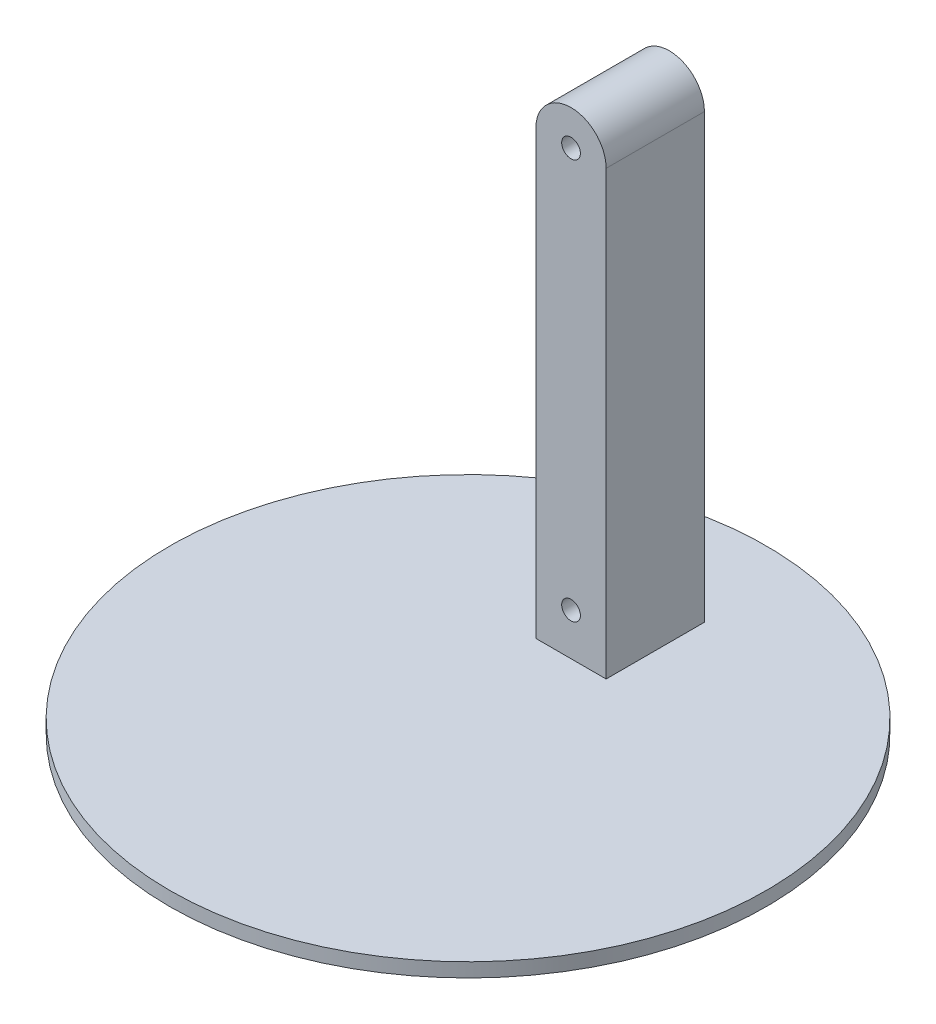
SolidWorks part; units mm, degrees
ref_plane "Front Plane" through (0, 0, 0) normal (0, 0, 1) x (1, 0, 0)
ref_plane "Top Plane" through (0, 0, 0) normal (0, 1, 0) x (1, 0, 0)
ref_plane "Right Plane" through (0, 0, 0) normal (1, 0, 0) x (0, 0, -1)
sketch "Sketch1" plane through (0, 0, 0) normal (0, 1, 0) x (1, 0, 0)
  circle A0 centre (0, 0) radius 127.5
  dimension "D1" = 255
extrude "Boss-Extrude1" add sketch "Sketch1" along normal blind 6 from offset 195 offset against normal yes
sketch "Sketch2" plane through (0, 0, 0) normal (0, 0, 1) x (1, 0, 0)
  line L0 (-15, 0) -> (-15, -189)
  line L1 (127.5, -189) -> (-127.5, -189) construction
  line L2 (-15, -189) -> (15, -189)
  line L3 (15, -189) -> (15, 0)
  circle A0 centre (0, 0) radius 4
  circle A1 centre (0, -171) radius 4
  arc A2 (15, 0) -> (-15, 0) centre (0, 0) ccw
  dimension "D1" = 8
  dimension "D2" = 30
  dimension "D3" = 18
extrude "Boss-Extrude2" add sketch "Sketch2" along normal mid plane 42 from offset 65
equation "\"flywheel_top_surface_to_center\" = 195mm"
equation "\"spine_center_distance\"= 65mm"
equation "\"spine_depth\"= 42mm"
equation "\"D19@Boss-Extrude1\"=\"flywheel_top_surface_to_center\""
equation "\"D19@Boss-Extrude2\"=\"spine_center_distance\""
equation "\"D1@Boss-Extrude2\"=\"spine_depth\""
